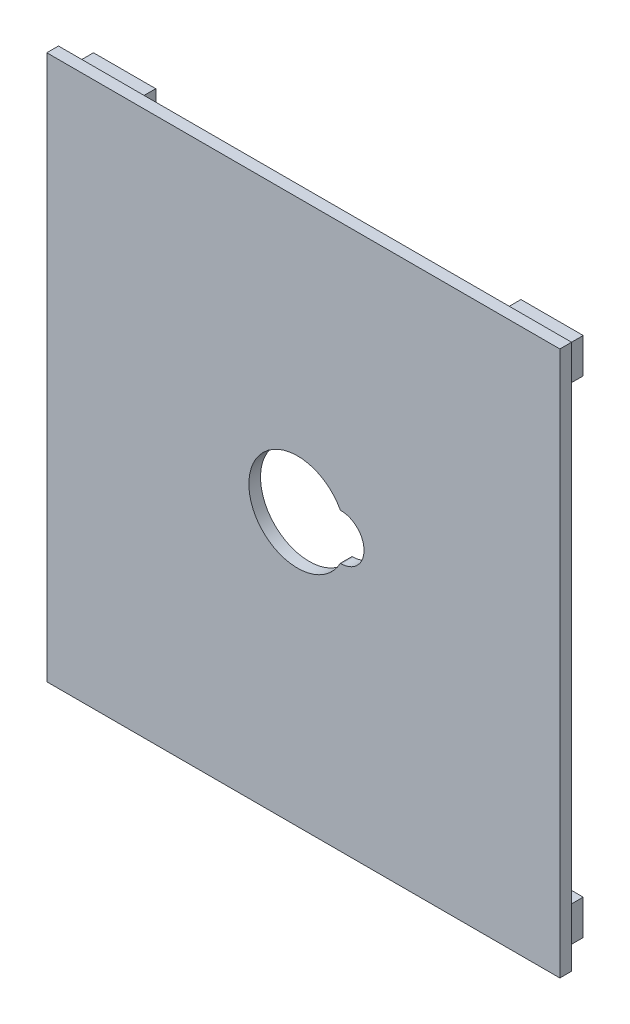
SolidWorks part; units mm, degrees
ref_plane "Front Plane" through (0, 0, 0) normal (0, 0, 1) x (1, 0, 0)
ref_plane "Top Plane" through (0, 0, 0) normal (0, 1, 0) x (1, 0, 0)
ref_plane "Right Plane" through (0, 0, 0) normal (1, 0, 0) x (0, 0, -1)
sketch "Sketch1" plane through (0, 0, 0) normal (0, 0, 1) x (1, 0, 0)
  line L0 (-10.75, -9.75) -> (121.1, -9.75) construction
  line L2 (121.1, -9.75) -> (55.175, -9.75)
  line L3 (121.1, -9.75) -> (121.1, 60.25)
  line L4 (121.1, 60.25) -> (55.175, 60.25)
  line L5 (55.175, -9.75) -> (55.175, 60.25)
  point P7 (0, 0)
  point P8 (55.175, -9.75)
  point P11 (0, 0)
extrude "Boss-Extrude1" add sketch "Sketch1" along normal blind 1.5 contours L5 L2 L3 L4
sketch "Sketch2" plane through (0, 0, 1.5) normal (0, 0, 1) x (1, 0, 0)
  line L4 (92.8975, 22.3) -> (92.9875, 22.3)
  line L5 (92.9875, 28.2) -> (92.8975, 28.2)
  line L6 (92.8975, 22.3) -> (92.9875, 22.3)
  line L7 (92.9875, 28.2) -> (92.8975, 28.2)
  arc A8 (92.9875, 22.3) -> (92.9875, 28.2) centre (92.9875, 25.25) ccw
  arc A9 (92.8975, 28.2) -> (92.8975, 22.3) centre (87.3875, 25.25) ccw
  arc A10 (92.9875, 22.3) -> (92.9875, 28.2) centre (92.9875, 25.25) ccw
  arc A11 (92.8975, 28.2) -> (92.8975, 22.3) centre (87.3875, 25.25) ccw
  dimension "D1" = 0.25
extrude "Cut-Extrude1" cut sketch "Sketch2" against normal up to next
ref_plane "Plane2" through (88.1375, 0, 0) normal (1, 0, 0) x (0, 0, -1)
ref_plane "Plane1" through (0, 25.25, 0) normal (0, 1, 0) x (1, 0, 0)
sketch "Sketch4" plane through (0, 0, 0) normal (0, 0, -1) x (-1, 0, 0)
  line L0 (-118.1, 57.25) -> (-118.1, 55.75)
  line L1 (-119.6, 58.75) -> (-111.6, 58.75)
  line L2 (-119.6, 58.75) -> (-119.6, 54.25)
  line L3 (-119.6, 54.25) -> (-111.6, 54.25)
  line L4 (-111.6, 58.75) -> (-111.6, 54.25)
  line L5 (-119.6, 58.75) -> (-119.6, 60.25) construction
  line L6 (-118.1, 55.75) -> (-113.1, 55.75)
  line L8 (-113.1, 57.25) -> (-113.1, 55.75)
  line L9 (-118.1, 57.25) -> (-113.1, 57.25)
  line L10 (-119.6, 58.75) -> (-121.1, 58.75) construction
  line L12 (-121.1, 60.25) -> (-55.175, 60.25) construction
  line L13 (-121.1, -9.75) -> (-121.1, 60.25) construction
  point P8 (-119.5596, 60.25)
  point P12 (-121.1, 58.75)
  dimension "D1" = 1.5
  dimension "D2" = 5
  dimension "D3" = 1.5
extrude "Boss-Extrude2" add sketch "Sketch4" along normal blind 3
mirror "Mirror1" about plane through (88.1375, 0, 0) normal (1, 0, 0) of "Boss-Extrude2"
mirror "Mirror2" about plane through (0, 25.25, 0) normal (0, 1, 0) of "Mirror1", "Boss-Extrude2"
sketch "Sketch3" [suppressed] plane through (121.1, 0, 0) normal (1, 0, 0) x (0, 0, -1)
  line L0 (0, -9.75) -> (0, 60.25) construction
  line L1 (-1.5, 60.25) -> (6, 60.25)
  line L2 (-1.5, 60.25) -> (-1.5, 61.75)
  line L3 (-1.5, 61.75) -> (6, 61.75)
  line L4 (6, 60.25) -> (6, 61.75)
  line L5 (6, 60.25) -> (4.5, 58.75)
  line L7 (4.5, 58.75) -> (4.5, 60.25)
  dimension "D1" = 1.5
  dimension "D2" = 6
  dimension "D3" = 45
equation "\"D1@Boss-Extrude2\"=1.50mm+.25"
